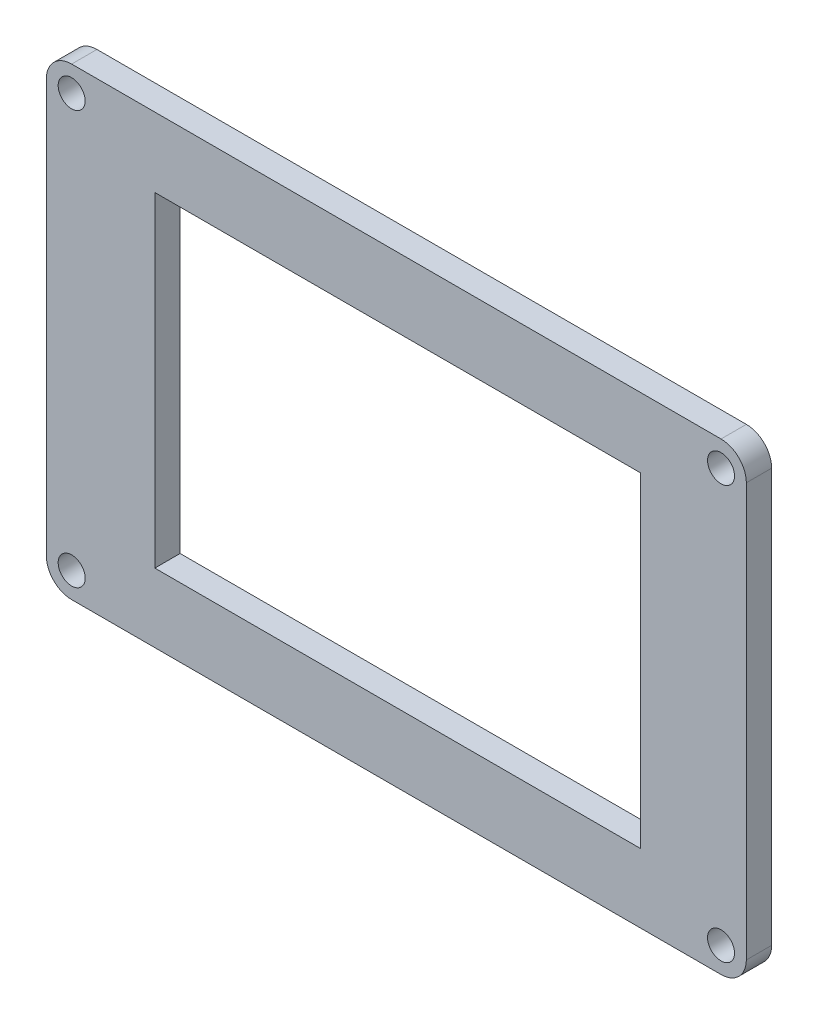
SolidWorks part; units mm, degrees
ref_plane "前视基准面" through (0, 0, 0) normal (0, 0, 1) x (1, 0, 0)
ref_plane "上视基准面" through (0, 0, 0) normal (0, 1, 0) x (1, 0, 0)
ref_plane "右视基准面" through (0, 0, 0) normal (1, 0, 0) x (0, 0, -1)
other "Configuration Table"
sketch "草图1" plane through (0, 0, 0) normal (0, 0, 1) x (1, 0, 0)
  line L0 (38.5, 3) -> (38.5, -57.9371) construction
  line L1 (0, -52) -> (77, -52)
  line L2 (-3, -49) -> (-3, 0)
  line L3 (0, 3) -> (77, 3)
  line L4 (80, -49) -> (80, 0)
  line L5 (80, -24.5) -> (-16.7766, -24.5) construction
  line L7 (16.5, -41.5) -> (60.5, -41.5)
  line L8 (13.5, -38.5) -> (13.5, -10.5)
  line L9 (16.5, -7.5) -> (60.5, -7.5)
  line L10 (63.5, -38.5) -> (63.5, -10.5)
  line L11 (13.5, -41.5) -> (63.5, -7.5) construction
  line L12 (13.5, -7.5) -> (63.5, -41.5) construction
  circle A0 centre (0, 0) radius 1.6
  circle A1 centre (77, 0) radius 1.6
  circle A2 centre (0, -49) radius 1.6
  circle A3 centre (77, -49) radius 1.6
  arc A4 (0, -52) -> (-3, -49) centre (0, -49) cw
  arc A5 (77, -52) -> (80, -49) centre (77, -49) ccw
  arc A6 (77, 3) -> (80, 0) centre (77, 0) cw
  arc A7 (-3, 0) -> (0, 3) centre (0, 0) cw
  arc A8 (16.5, -41.5) -> (13.5, -38.5) centre (16.5, -38.5) cw
  arc A9 (60.5, -41.5) -> (63.5, -38.5) centre (60.5, -38.5) ccw
  arc A10 (60.5, -7.5) -> (63.5, -10.5) centre (60.5, -10.5) cw
  arc A11 (13.5, -10.5) -> (16.5, -7.5) centre (16.5, -10.5) cw
  point P11 (-3, -52)
  point P20 (80, 3)
  point P23 (-3, 3)
  point P27 (38.5, -24.5)
  point P33 (38.5, 3)
  point P34 (80, -24.5)
  dimension "D1" = 3.2
  dimension "D2" = 3.2
  dimension "D3" = 3.2
  dimension "D4" = 3.2
  dimension "D9" = 3
  dimension "D14" = 3
  dimension "D5" = 49
  dimension "D6" = 77
  dimension "D7" = 83
  dimension "D8" = 55
  dimension "D10" = 3
  dimension "D11" = 3
  dimension "D12" = 50
  dimension "D13" = 34
extrude "凸台-拉伸1" add sketch "草图1" along normal blind 3
sketch "草图3" plane through (0, 0, 3) normal (0, 0, 1) x (1, 0, 0)
  line L1 (9.8603, -43.8309) -> (67.4644, -43.8309)
  line L2 (9.8603, -43.8309) -> (9.8603, -5.2567)
  line L3 (9.8603, -5.2567) -> (67.4644, -5.2567)
  line L4 (67.4644, -43.8309) -> (67.4644, -5.2567)
extrude "切除-拉伸1" cut sketch "草图3" against normal blind 10
